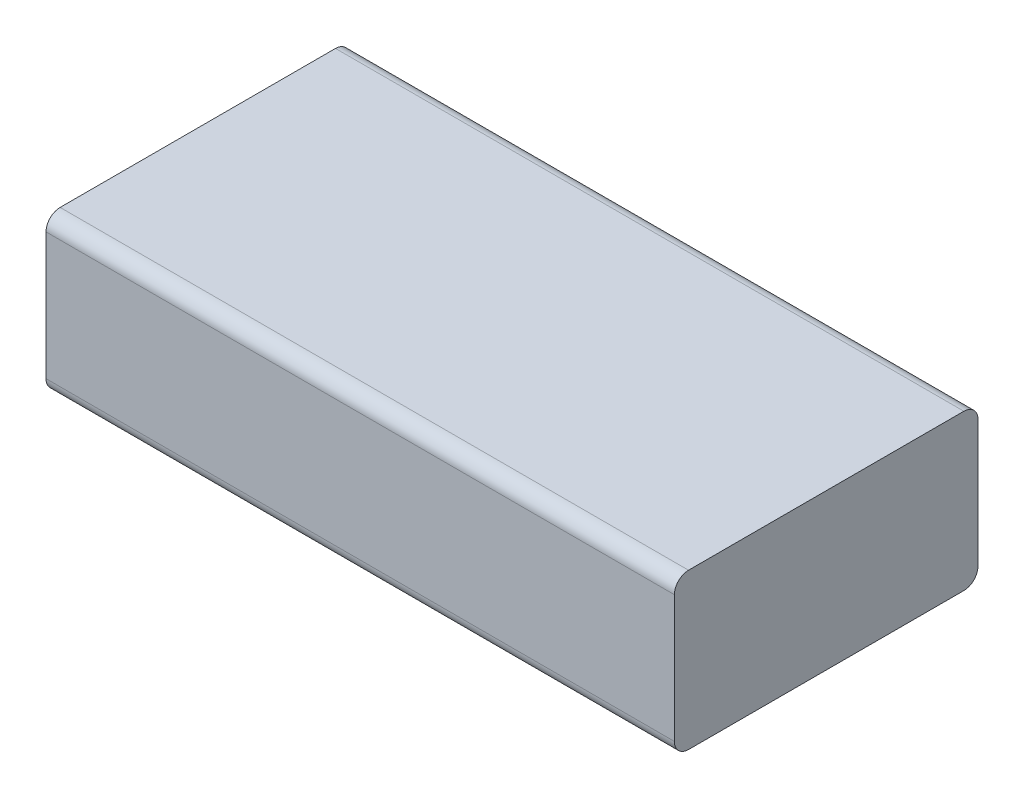
SolidWorks part; units mm, degrees
material "PVAL"
ref_plane "Front Plane" through (0, 0, 0) normal (0, 0, 1) x (1, 0, 0)
ref_plane "Top Plane" through (0, 0, 0) normal (0, 1, 0) x (1, 0, 0)
ref_plane "Right Plane" through (0, 0, 0) normal (1, 0, 0) x (0, 0, -1)
sketch "Sketch1" plane through (0, 0, 0) normal (0, 1, 0) x (1, 0, 0)
  line L0 (-44.5, -21.5) -> (44.5, 21.5) construction
  line L1 (-44.5, 21.5) -> (44.5, 21.5)
  line L2 (-44.5, 21.5) -> (-44.5, -21.5)
  line L3 (-44.5, -21.5) -> (44.5, -21.5)
  line L4 (44.5, 21.5) -> (44.5, -21.5)
  line L5 (-44.5, 21.5) -> (44.5, -21.5) construction
  point P4 (0, 0)
  point P5 (0, 0)
  dimension "D1" = 89
  dimension "D2" = 43
extrude "Boss-Extrude1" add sketch "Sketch1" along normal blind 22
fillet "Fillet1" radius 2 4 edges at (0, 0, -21.5) (0, 22, -21.5) (0, 0, 21.5) (0, 22, 21.5)
